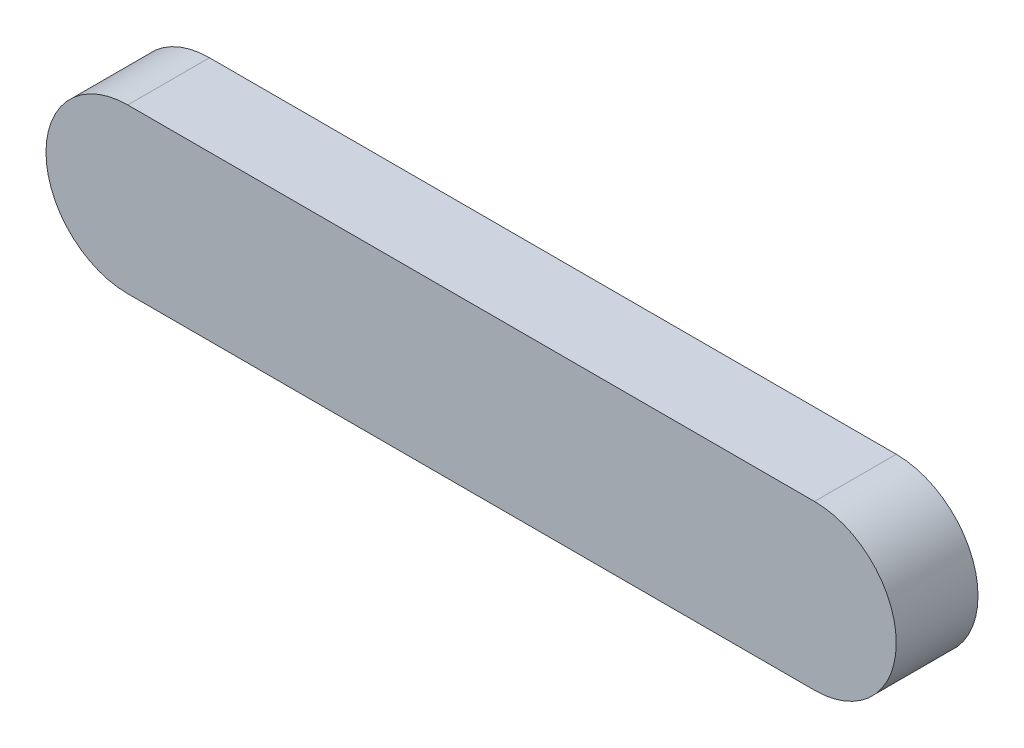
SolidWorks part; units mm, degrees
ref_plane "Front Plane" through (0, 0, 0) normal (0, 0, 1) x (1, 0, 0)
ref_plane "Top Plane" through (0, 0, 0) normal (0, 1, 0) x (1, 0, 0)
ref_plane "Right Plane" through (0, 0, 0) normal (1, 0, 0) x (0, 0, -1)
sketch "Sketch1" plane through (0, 0, 0) normal (0, 0, 1) x (1, 0, 0)
  line L0 (-21, 0) -> (21, 0) construction
  line L1 (-21, 5) -> (21, 5)
  line L2 (-21, -5) -> (21, -5)
  arc A0 (-21, 5) -> (-21, -5) centre (-21, 0) ccw
  arc A1 (21, -5) -> (21, 5) centre (21, 0) ccw
  point P2 (0, 0)
  dimension "D2" = 5
  dimension "D1" = 42
extrude "Boss-Extrude1" add sketch "Sketch1" along normal mid plane 5
